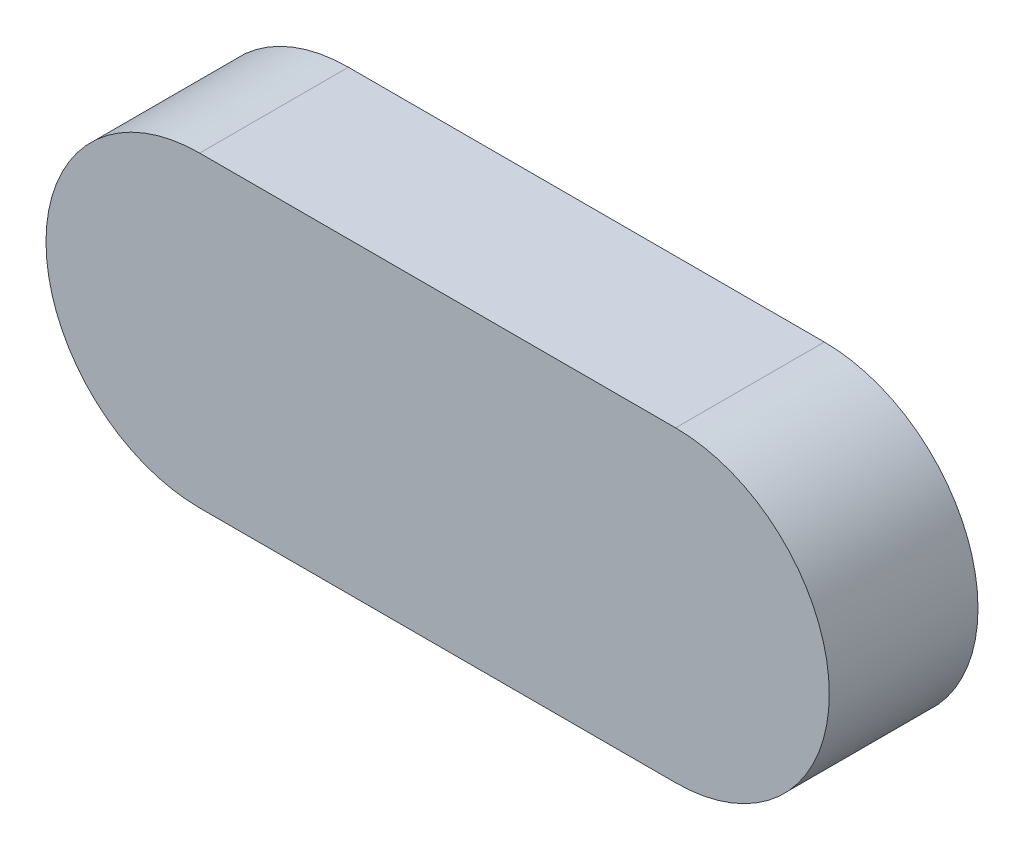
SolidWorks part; units mm, degrees
material "Plain Carbon Steel"
ref_plane "Front Plane" through (0, 0, 0) normal (0, 0, 1) x (1, 0, 0)
ref_plane "Top Plane" through (0, 0, 0) normal (0, 1, 0) x (1, 0, 0)
ref_plane "Right Plane" through (0, 0, 0) normal (1, 0, 0) x (0, 0, -1)
sketch "Sketch1" plane through (0, 0, 0) normal (0, 0, 1) x (1, 0, 0)
  line L0 (-12, 0) -> (12, 0) construction
  line L1 (-12, 7.75) -> (12, 7.75)
  line L2 (-12, -7.75) -> (12, -7.75)
  arc A0 (-12, 7.75) -> (-12, -7.75) centre (-12, 0) ccw
  arc A1 (12, -7.75) -> (12, 7.75) centre (12, 0) ccw
  point P2 (0, 0)
  dimension "D2" = 7.75
  dimension "D1" = 24
extrude "Boss-Extrude1" add sketch "Sketch1" along normal mid plane 7.5
